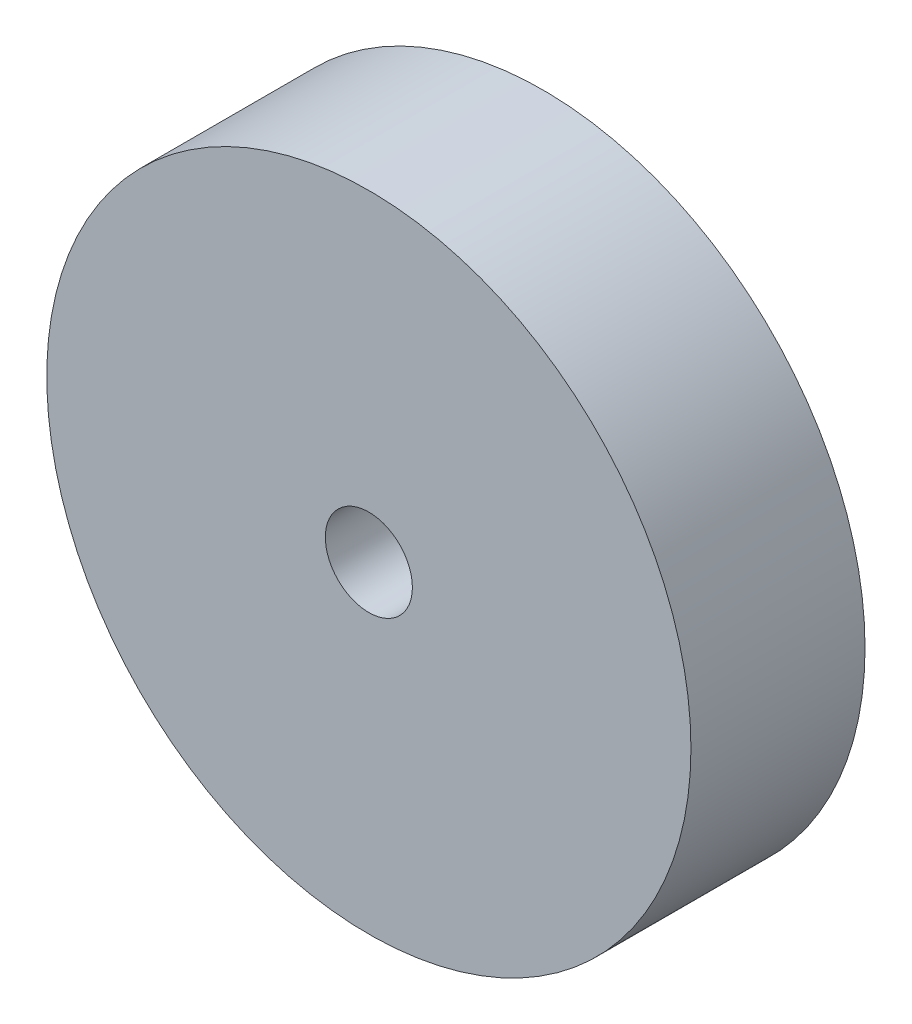
SolidWorks part; units mm, degrees
ref_plane "Plan de face" through (0, 0, 0) normal (0, 0, 1) x (1, 0, 0)
ref_plane "Plan de dessus" through (0, 0, 0) normal (0, 1, 0) x (1, 0, 0)
ref_plane "Plan de droite" through (0, 0, 0) normal (1, 0, 0) x (0, 0, -1)
sketch "Esquisse1" plane through (0, 0, 0) normal (0, 0, 1) x (1, 0, 0)
  circle A0 centre (0, 0) radius 9.25
  circle A1 centre (0, 0) radius 0.75
  dimension "D1" = 18.5
  dimension "D2" = 1.5
extrude "Boss.-Extru.1" add sketch "Esquisse1" along normal blind 5
hole_wizard "Trou taraudé M3x0.51" positions "Esquisse3D2" profile "Esquisse3" tap size "M3x0.5" standard "Ansi Metric" end condition through all
sketch3d "Esquisse3D2"
  line L0 (0, 0, 5) -> (0, 0, 0) construction
  point P3 (0, 0, 5)
sketch "Esquisse3" plane through (0, 0, 5) normal (1, 0, 0) x (0, -1, 0)
  line L0 (0, 0) -> (0, 5)
  line L1 (0, 5) -> (1.25, 5)
  line L2 (1.25, 5) -> (1.25, 0)
  line L5 (1.25, 0) -> (0, 0)
  line L11 (0, -6.35) -> (0, 107.95) construction
  dimension "Diamètre du trou pour taraudage jusqu'au prochain" = 2.5
  dimension "Profondeur du trou pour taraudage jusqu'au prochain" = 5
cosmetic thread "Filetage de perçage1"
equation "\"1.5mml\"=15"
